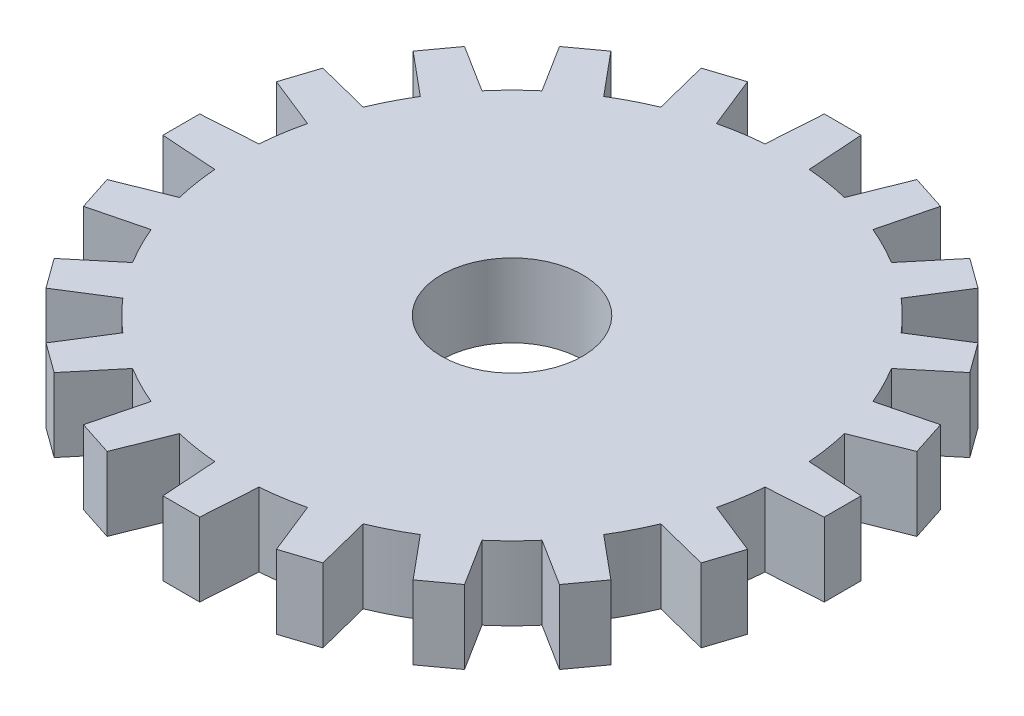
SolidWorks part; units mm, degrees
ref_plane "Front Plane" through (0, 0, 0) normal (0, 0, 1) x (1, 0, 0)
ref_plane "Top Plane" through (0, 0, 0) normal (0, 1, 0) x (1, 0, 0)
ref_plane "Right Plane" through (0, 0, 0) normal (1, 0, 0) x (0, 0, -1)
sketch "Sketch1" plane through (0, 0, 0) normal (0, 1, 0) x (1, 0, 0)
  line L0 (-3, 37.3798) -> (-2.5, 44.9305)
  line L1 (3, 37.3798) -> (2.5, 44.9305)
  line L2 (0, 44.9305) -> (0, 0) construction
  line L3 (0, 0) -> (22.5041, 0) construction
  line L4 (-2.5, 44.9305) -> (2.5, 44.9305)
  line L5 (8.6978, 36.4774) -> (11.5066, 43.504)
  line L6 (14.4042, 34.6233) -> (16.2619, 41.9589)
  line L7 (11.5066, 43.504) -> (16.2619, 41.9589)
  line L8 (19.5442, 32.0043) -> (24.3869, 37.819)
  line L9 (24.3984, 28.4775) -> (28.432, 34.8801)
  line L10 (24.3869, 37.819) -> (28.432, 34.8801)
  line L11 (28.4775, 24.3984) -> (34.8801, 28.432)
  line L12 (32.0043, 19.5442) -> (37.819, 24.3869)
  line L13 (34.8801, 28.432) -> (37.819, 24.3869)
  line L14 (34.6233, 14.4042) -> (41.9589, 16.2619)
  line L15 (36.4774, 8.6978) -> (43.504, 11.5066)
  line L16 (41.9589, 16.2619) -> (43.504, 11.5066)
  line L17 (37.3798, 3) -> (44.9305, 2.5)
  line L18 (37.3798, -3) -> (44.9305, -2.5)
  line L19 (44.9305, 2.5) -> (44.9305, -2.5)
  line L20 (36.4774, -8.6978) -> (43.504, -11.5066)
  line L21 (34.6233, -14.4042) -> (41.9589, -16.2619)
  line L22 (43.504, -11.5066) -> (41.9589, -16.2619)
  line L23 (32.0043, -19.5442) -> (37.819, -24.3869)
  line L24 (28.4775, -24.3984) -> (34.8801, -28.432)
  line L25 (37.819, -24.3869) -> (34.8801, -28.432)
  line L26 (24.3984, -28.4775) -> (28.432, -34.8801)
  line L27 (19.5442, -32.0043) -> (24.3869, -37.819)
  line L28 (28.432, -34.8801) -> (24.3869, -37.819)
  line L29 (14.4042, -34.6233) -> (16.2619, -41.9589)
  line L30 (8.6978, -36.4774) -> (11.5066, -43.504)
  line L31 (16.2619, -41.9589) -> (11.5066, -43.504)
  line L32 (3, -37.3798) -> (2.5, -44.9305)
  line L33 (-3, -37.3798) -> (-2.5, -44.9305)
  line L34 (2.5, -44.9305) -> (-2.5, -44.9305)
  line L35 (-8.6978, -36.4774) -> (-11.5066, -43.504)
  line L36 (-14.4042, -34.6233) -> (-16.2619, -41.9589)
  line L37 (-11.5066, -43.504) -> (-16.2619, -41.9589)
  line L38 (-19.5442, -32.0043) -> (-24.3869, -37.819)
  line L39 (-24.3984, -28.4775) -> (-28.432, -34.8801)
  line L40 (-24.3869, -37.819) -> (-28.432, -34.8801)
  line L41 (-28.4775, -24.3984) -> (-34.8801, -28.432)
  line L42 (-32.0043, -19.5442) -> (-37.819, -24.3869)
  line L43 (-34.8801, -28.432) -> (-37.819, -24.3869)
  line L44 (-34.6233, -14.4042) -> (-41.9589, -16.2619)
  line L45 (-36.4774, -8.6978) -> (-43.504, -11.5066)
  line L46 (-41.9589, -16.2619) -> (-43.504, -11.5066)
  line L47 (-37.3798, -3) -> (-44.9305, -2.5)
  line L48 (-37.3798, 3) -> (-44.9305, 2.5)
  line L49 (-44.9305, -2.5) -> (-44.9305, 2.5)
  line L50 (-36.4774, 8.6978) -> (-43.504, 11.5066)
  line L51 (-34.6233, 14.4042) -> (-41.9589, 16.2619)
  line L52 (-43.504, 11.5066) -> (-41.9589, 16.2619)
  line L53 (-32.0043, 19.5442) -> (-37.819, 24.3869)
  line L54 (-28.4775, 24.3984) -> (-34.8801, 28.432)
  line L55 (-37.819, 24.3869) -> (-34.8801, 28.432)
  line L56 (-24.3984, 28.4775) -> (-28.432, 34.8801)
  line L57 (-19.5442, 32.0043) -> (-24.3869, 37.819)
  line L58 (-28.432, 34.8801) -> (-24.3869, 37.819)
  line L59 (-14.4042, 34.6233) -> (-16.2619, 41.9589)
  line L60 (-8.6978, 36.4774) -> (-11.5066, 43.504)
  line L61 (-16.2619, 41.9589) -> (-11.5066, 43.504)
  circle A0 centre (0, 0) radius 45
  circle A1 centre (0, 0) radius 37.5
  point P9 (0, 37.5)
  point P90 (0, 0)
  dimension "D1" = 90
  dimension "D2" = 75
  dimension "D3" = 5
  dimension "D4" = 3
  dimension "D5" = 3
  dimension "D6" = 20
extrude "Boss-Extrude1" add sketch "Sketch1" along normal blind 10 contours A1 | A1 L60 L61 L59 | A1 L57 L58 L56 | A1 L54 L55 L53 | A1 L51 L52 L50 | A1 L48 L49 L47 | A1 L45 L46 L44 | A1 L42 L43 L41 | A1 L39 L40 L38 | A1 L36 L37 L35 | A1 L33 L34 L32 | A1 L30 L31 L29 | A1 L27 L28 L26 | A1 L24 L25 L23 | A1 L21 L22 L20 | A1 L18 L19 L17 | A1 L15 L16 L14 | A1 L12 L13 L11 | A1 L9 L10 L8 | A1 L6 L7 L5 | A1 L1 L4 L0
sketch "Sketch2" plane through (0, 10, 0) normal (0, 1, 0) x (1, 0, 0)
  circle A0 centre (0, 0) radius 9.59
  dimension "D1" = 19.18
extrude "Cut-Extrude1" cut sketch "Sketch2" against normal blind 10
